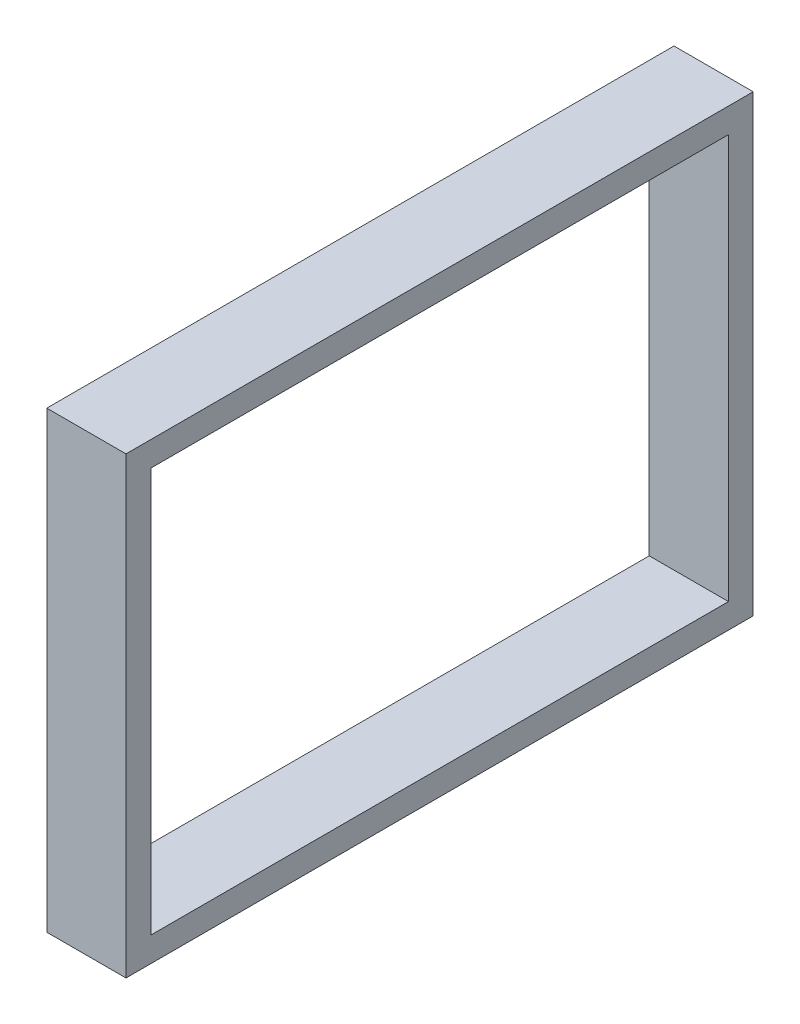
SolidWorks part; units mm, degrees
material "未指定"
ref_plane "正面" through (0, 0, 0) normal (0, 0, 1) x (1, 0, 0)
ref_plane "平面" through (0, 0, 0) normal (0, 1, 0) x (1, 0, 0)
ref_plane "右側面" through (0, 0, 0) normal (1, 0, 0) x (0, 0, -1)
sketch "ｽｹｯﾁ1" plane through (0, 0, 0) normal (1, 0, 0) x (0, 0, -1)
  line L0 (6.5, -13.75) -> (-31.5, -13.75)
  line L1 (-31.5, -13.75) -> (-31.5, 13.75)
  line L2 (-31.5, 13.75) -> (6.5, 13.75)
  line L3 (6.5, 13.75) -> (6.5, -13.75)
  line L4 (5, -12.25) -> (-30, -12.25)
  line L5 (-30, -12.25) -> (-30, 12.25)
  line L6 (-30, 12.25) -> (5, 12.25)
  line L7 (5, 12.25) -> (5, -12.25)
  dimension "D1" = 31.5
  dimension "D2" = 6.5
  dimension "D3" = 30
  dimension "D4" = 5
  dimension "D5" = 13.75
  dimension "D6" = 13.75
  dimension "D7" = 12.25
  dimension "D8" = 12.25
extrude "バンド" add sketch "ｽｹｯﾁ1" along normal mid plane 4.8
equation "\"PLATE_T\" = 10"
equation "\"BAND_OUT\" = 25"
equation "\"BAND_T\" = 1.5"
equation "\"D1@ｽｹｯﾁ1\" = \"PLATE_T\" / 2 + \"BAND_OUT\" + \"BAND_T\""
equation "\"D2@ｽｹｯﾁ1\" = \"PLATE_T\" / 2 + \"BAND_T\""
equation "\"D3@ｽｹｯﾁ1\" = \"PLATE_T\" / 2 + \"BAND_OUT\""
equation "\"D4@ｽｹｯﾁ1\" = \"PLATE_T\" / 2"
equation "\"TIE_Y2\" = -92"
equation "\"TIE_YC\" = -79"
equation "\"D5@ｽｹｯﾁ1\" = abs( \"TIE_Y2\" - \"TIE_YC\" - \"BAND_T\" / 2 )"
equation "\"TIE_Y1\" = -66"
equation "\"D6@ｽｹｯﾁ1\" = \"TIE_Y1\" - \"TIE_YC\" + \"BAND_T\" / 2"
equation "\"D7@ｽｹｯﾁ1\" = abs( \"TIE_Y2\" - \"TIE_YC\" + \"BAND_T\" / 2 )"
equation "\"D8@ｽｹｯﾁ1\" = \"TIE_Y1\" - \"TIE_YC\" - \"BAND_T\" / 2"
equation "\"BAND_W\" = 4.8"
equation "\"D1@バンド\" = \"BAND_W\""
